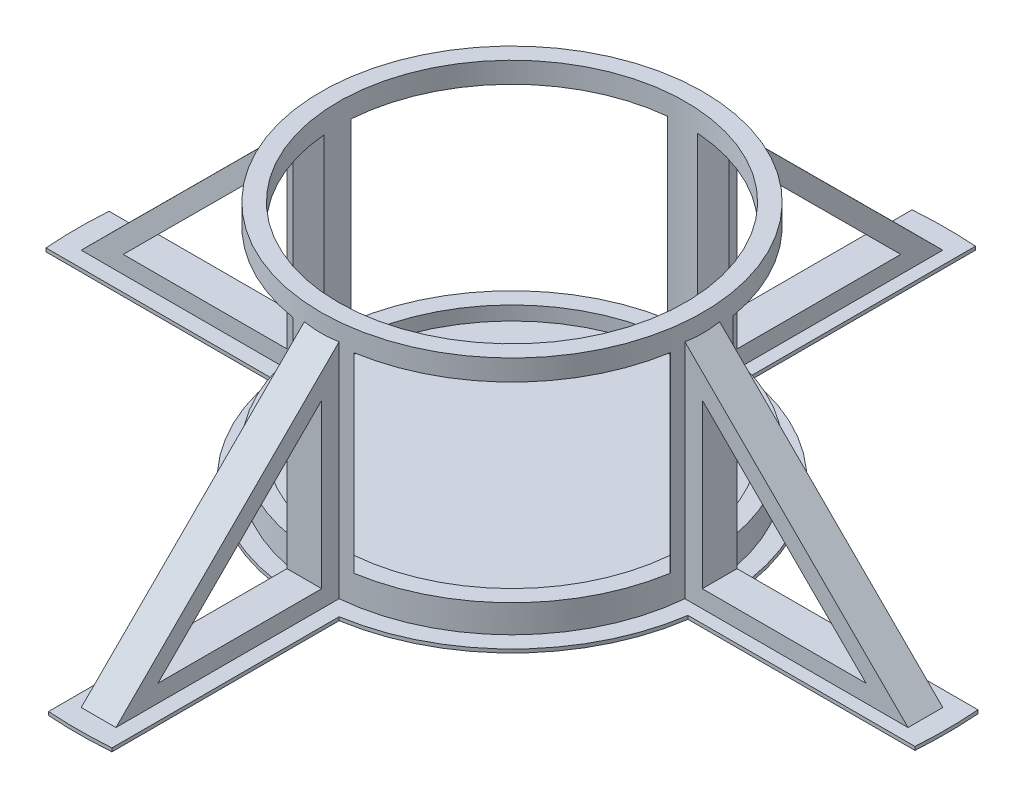
SolidWorks part; units mm, degrees
ref_plane "Front Plane" through (0, 0, 0) normal (0, 0, 1) x (1, 0, 0)
ref_plane "Top Plane" through (0, 0, 0) normal (0, 1, 0) x (1, 0, 0)
ref_plane "Right Plane" through (0, 0, 0) normal (1, 0, 0) x (0, 0, -1)
sketch "Sketch2" plane through (0, 0, 0) normal (0, 1, 0) x (1, 0, 0)
  circle A0 centre (0, 0) radius 55
  dimension "D1" = 110
extrude "Boss-Extrude1" add sketch "Sketch2" along normal blind 70 contours A0
shell "Shell1" thickness 5
sketch "Sketch4" plane through (0, 0, 0) normal (0, 1, 0) x (1, 0, 0)
  circle A0 centre (0, 0) radius 125
  dimension "D1" = 250
extrude "Boss-Extrude2" add sketch "Sketch4" along normal blind 1
sketch "Sketch3" plane through (0, 0, 0) normal (0, 0, 1) x (1, 0, 0)
  line L1 (119, 1) -> (55, 1) construction
  line L3 (55, 64.819) -> (119, 1)
  line L4 (55, 1) -> (55, 70) construction
  line L5 (55, 64.819) -> (55, 1) construction
rib "Rib7" sketch "Sketch3" sketch "Sketch3" thickness 10 extrusion direction parallel to sketch draft on no parameters "D1"=10
pattern_circular "CirPattern1" count 4 every 90 about axis through (0, 0, 0) along (0, 1, 0) of "Rib7"
sketch "Sketch5" plane through (0, 1, 0) normal (0, 1, 0) x (1, 0, 0)
  line L0 (9.4931, -59.2442) -> (9.4931, -129.6529)
  line L1 (59.3646, -8.7092) -> (129.7079, -8.7092)
  line L2 (5, -54.7723) -> (5, -119) construction
  line L3 (54.7723, -5) -> (119, -5) construction
  arc A0 (9.4931, -59.2442) -> (59.3646, -8.7092) centre (0, 0) ccw
  arc A1 (9.4931, -129.6529) -> (129.7079, -8.7092) centre (0, 0) ccw
  dimension "D1" = 120
  dimension "D2" = 130
  dimension "D3" = 70.3434
  dimension "D4" = 70.4087
extrude "Cut-Extrude1" cut sketch "Sketch5" against normal blind 1 contours A0 L1 A1 L0
pattern_circular "CirPattern2" count 4 every 90 about axis through (0, 0, 0) along (0, 1, 0) of "Cut-Extrude1"
sketch "Sketch7" plane through (5, 0, 0) normal (1, 0, 0) x (0, 0, -1)
  line L0 (59.7723, 52.9992) -> (106.9047, 6)
  line L1 (106.9047, 6) -> (59.7723, 6)
  line L2 (59.7723, 6) -> (59.7723, 52.9992)
  line L3 (54.7723, 65.0461) -> (119, 1) construction
  line L4 (54.7723, 1) -> (119, 1) construction
  line L5 (54.7723, 1) -> (54.7723, 65.0461) construction
  line L6 (59.3646, 1) -> (124.6962, 1) construction
  dimension "D1" = 5
  dimension "D2" = 5
  dimension "D3" = 5
extrude "Cut-Extrude2" cut sketch "Sketch7" against normal through all
pattern_circular "CirPattern3" count 4 every 90 about axis through (0, 0, 0) along (0, 1, 0) of "Cut-Extrude2"
sketch "Sketch9" plane through (0, 0, 0) normal (1, 0, 0) x (0, 0, -1)
  line L1 (7.9237, 64.3724) -> (52.7338, 64.3724)
  line L2 (7.9237, 64.3724) -> (7.9237, 5.6452)
  line L3 (7.9237, 5.6452) -> (52.7338, 5.6452)
  line L4 (52.7338, 64.3724) -> (52.7338, 5.6452)
ref_plane "Plane2" through (0, 0, 0) normal (-0.7024, 0, 0.7118) x (0.7118, 0, 0.7024)
sketch "Sketch10" plane through (0, 0, 0) normal (-0.7024, 0, 0.7118) x (0.7118, 0, 0.7024)
  line L0 (-35.4729, 1) -> (-35.4729, 65.0461) construction
  line L1 (-32.4729, 64) -> (31.9142, 64)
  line L2 (-32.4729, 64) -> (-32.4729, 9)
  line L3 (-32.4729, 9) -> (31.9142, 9)
  line L4 (31.9142, 64) -> (31.9142, 9)
  line L5 (34.9142, 1) -> (34.9142, 65.0461) construction
  line L6 (50, 70) -> (-50, 70) construction
  dimension "D1" = 3
  dimension "D2" = 3
  dimension "D3" = 6
  dimension "D4" = 55
extrude "Cut-Extrude3" cut sketch "Sketch10" against normal through all both and the other way through all
pattern_circular "CirPattern4" count 2 every 90 about axis through (0, 70, 0) along (0, 1, 0) of "Cut-Extrude3"
